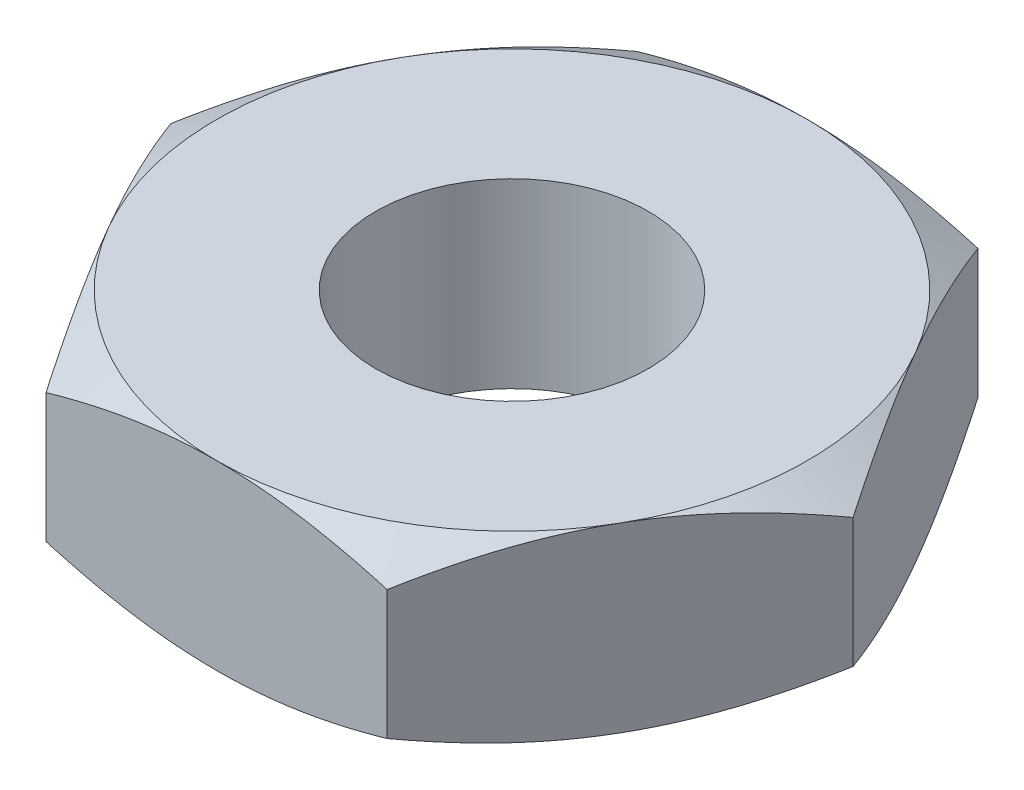
SolidWorks part; units mm, degrees
ref_plane "Front Plane" through (0, 0, 0) normal (0, 0, 1) x (1, 0, 0)
ref_plane "Top Plane" through (0, 0, 0) normal (0, 1, 0) x (1, 0, 0)
ref_plane "Right Plane" through (0, 0, 0) normal (1, 0, 0) x (0, 0, -1)
sketch "Sketch1" plane through (0, 0, 0) normal (0, 1, 0) x (1, 0, 0)
  line L1 (7.5056, -13) -> (15.0111, 0)
  line L2 (15.0111, 0) -> (7.5056, 13)
  line L3 (7.5056, 13) -> (-7.5056, 13)
  line L4 (-7.5056, 13) -> (-15.0111, 0)
  line L5 (-15.0111, 0) -> (-7.5056, -13)
  line L6 (-7.5056, -13) -> (7.5056, -13)
  circle A0 centre (0, 0) radius 13 construction
  dimension "D1" = 26
extrude "Boss-Extrude1" add sketch "Sketch1" along normal blind 8
sketch "Sketch2" plane through (0, 8, 0) normal (0, 1, 0) x (1, 0, 0)
  circle A0 centre (0, 0) radius 6
  dimension "D1" = 12
extrude "Cut-Extrude1" cut sketch "Sketch2" against normal through all
sketch "Sketch3" plane through (0, 8, 0) normal (0, 1, 0) x (1, 0, 0)
  circle A0 centre (0, 0) radius 13
extrude "Cut-Extrude2" cut sketch "Sketch3" against normal blind 8 draft 60 flip side to cut
ref_plane "Plane1" through (0, 4, 0) normal (0, 1, 0) x (1, 0, 0)
mirror "Mirror1" about plane through (0, 4, 0) normal (0, 1, 0) of "Cut-Extrude2"
